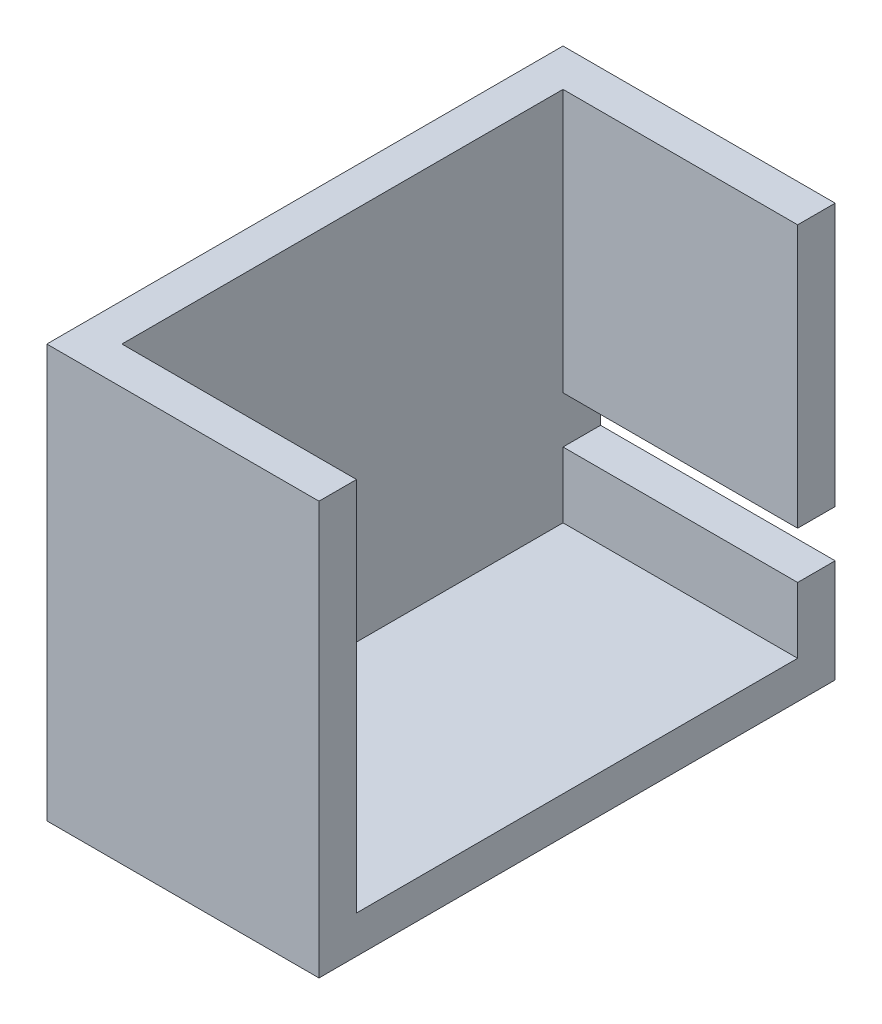
SolidWorks part; units mm, degrees
ref_plane "Спереди" through (0, 0, 0) normal (0, 0, 1) x (1, 0, 0)
ref_plane "Сверху" through (0, 0, 0) normal (0, 1, 0) x (1, 0, 0)
ref_plane "Справа" through (0, 0, 0) normal (1, 0, 0) x (0, 0, -1)
sketch "Эскиз2" plane through (0, 0, 0) normal (1, 0, 0) x (0, 0, -1)
  line L0 (-18.0559, 6.5) -> (18.0559, 6.5) construction
  line L1 (0, 0) -> (-23.5, 0)
  line L2 (0, 0) -> (0, 18)
  line L3 (0, 18) -> (-23.5, 18)
  line L4 (-23.5, 0) -> (-23.5, 18)
  line L5 (-19.1218, 4) -> (19.1218, 4) construction
  point P4 (0, 6.5)
  point P5 (0, 4)
  point P10 (0, 6.5)
  point P11 (6.0015, 6.5)
  point P13 (0, 4)
  point P14 (6.0889, 4)
  point P15 (3.7225, 6.5)
  point P16 (3.7225, 6.5)
  point P19 (6.0015, 6.5)
  dimension "D1" = 23.5
  dimension "D2" = 18
  dimension "D3" = 11.5
  dimension "D4" = 14
extrude "Бобышка-Вытянуть1" add sketch "Эскиз2" along normal blind 12.5
shell "Оболочка7" thickness 2
sketch "Эскиз4" plane through (0, 0, 0) normal (1, 0, 0) x (0, 0, -1)
  line L0 (0, 0) -> (0, 18) construction
  line L1 (0, 0) -> (0, 18) construction
  line L2 (0, 6) -> (0, 3.5)
  line L3 (0, 6) -> (2, 6)
  line L4 (2, 6) -> (2, 3.5)
  line L5 (2, 3.5) -> (0, 3.5)
  line L6 (2, -2) -> (2, 20) construction
  point P0 (0, 6)
  point P4 (0, 3.5)
  dimension "D1" = 12
  dimension "D2" = 14.5
extrude "Вырез-Вытянуть3" cut sketch "Эскиз4" along normal through all
sketch "Эскиз6" plane through (0, 18, 0) normal (0, -1, 0) x (1, 0, 0)
  line L0 (12.5, 23.5) -> (12.5, 0)
  line L1 (12.5, 0) -> (0, 0)
  line L2 (0, 0) -> (0, 23.5)
  line L3 (0, 23.5) -> (12.5, 23.5)
extrude "Вырез-Вытянуть4" cut sketch "Эскиз6" against normal through all
